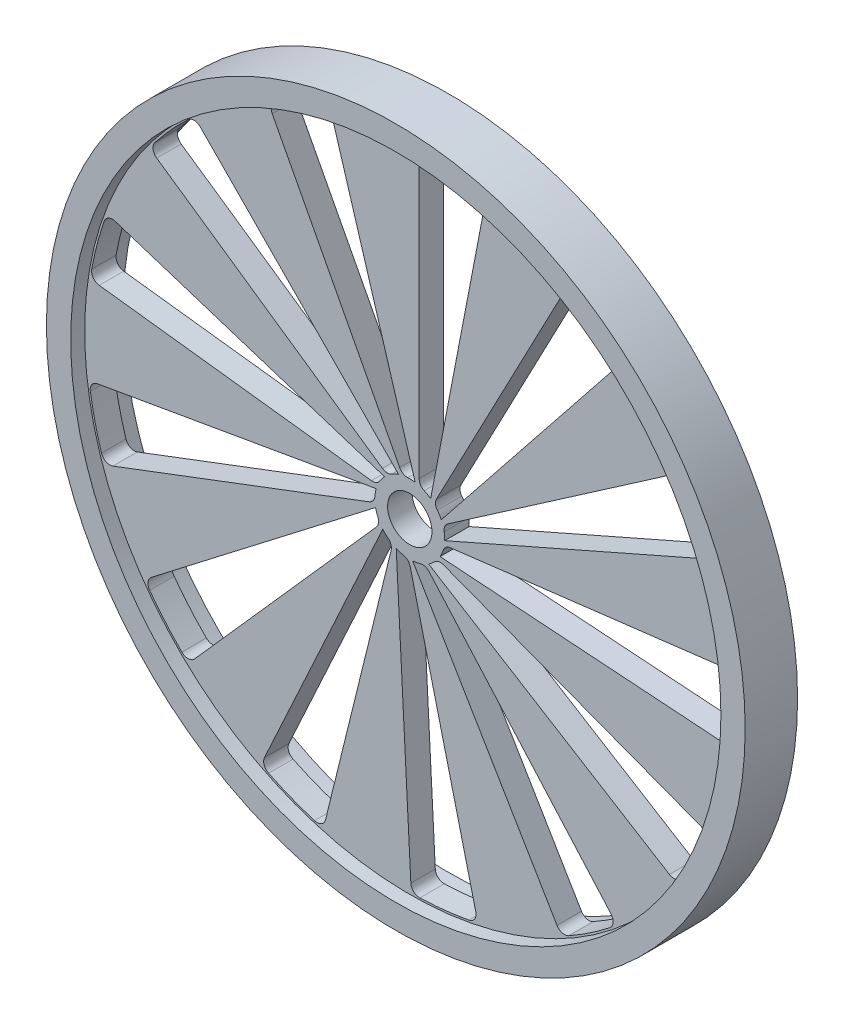
SolidWorks part; units mm, degrees
material "6061-T6 (SS)"
ref_plane "Front Plane" through (0, 0, 0) normal (0, 0, 1) x (1, 0, 0)
ref_plane "Top Plane" through (0, 0, 0) normal (0, 1, 0) x (1, 0, 0)
ref_plane "Right Plane" through (0, 0, 0) normal (1, 0, 0) x (0, 0, -1)
sketch "Sketch1" plane through (0, 0, 0) normal (0, 0, 1) x (1, 0, 0)
  line L0 (0, 319.656) -> (0, -338.2238) construction
  line L1 (-341.3059, 0) -> (522.3383, 0) construction
  line L2 (5.3734, 179.7008) -> (5.3734, 22.7463)
  line L3 (42.5198, 175.0831) -> (11.9457, 16.0406)
  line L4 (88.269, 156.6201) -> (15.3286, 17.6437)
  line L5 (119.0146, 135.2685) -> (18.0318, 8.6518)
  line L6 (150.9433, 97.6595) -> (21.7722, 8.4992)
  line L7 (168.2446, 64.4654) -> (19.9871, -0.7191)
  line L8 (179.0383, 16.3264) -> (23.2281, -2.5924)
  line L9 (178.9318, -21.1058) -> (17.3635, -9.9252)
  line L10 (166.1178, -68.747) -> (19.3627, -13.0901)
  line L11 (148.6278, -101.842) -> (10.7622, -16.8575)
  line L12 (115.1417, -138.0712) -> (11.0616, -20.589)
  line L13 (84.2751, -159.2474) -> (1.6954, -19.928)
  line L14 (37.788, -175.765) -> (0.2263, -23.3712)
  line L15 (0.6159, -180.1712) -> (-7.7598, -18.4333)
  line L16 (-48.2224, -173.1931) -> (-10.6608, -20.7994)
  line L17 (-83.1844, -159.8199) -> (-15.4374, -12.7157)
  line L18 (-123.1857, -130.9448) -> (-19.1056, -13.4626)
  line L19 (-147.9281, -102.8557) -> (-19.5784, -4.0851)
  line L20 (-169.9286, -58.6986) -> (-23.1736, -3.0418)
  line L21 (-178.7833, -22.3286) -> (-19.2342, 5.4814)
  line L22 (-177.7429, 26.9947) -> (-21.9328, 8.0759)
  line L23 (-168.6814, 63.3137) -> (-14.4837, 13.7921)
  line L24 (-144.8385, 106.5039) -> (-15.6674, 17.3435)
  line L25 (-119.9366, 134.4516) -> (-6.4152, 18.9432)
  line L26 (-78.7533, 161.6143) -> (-5.8129, 22.638)
  line L27 (-43.7158, 174.7883) -> (3.123, 19.7547)
  circle A0 centre (0, 0) radius 200
  circle A1 centre (0, 0) radius 12.7
  arc A3 (38.6544, 180.9167) -> (10.6615, 184.6925) centre (0, 0) ccw
  arc A4 (11.9457, 16.0406) -> (8.2987, 18.197) centre (0, 0) ccw
  arc A5 (42.5198, 175.0831) -> (38.6544, 180.9167) centre (37.6097, 176.027) ccw
  arc A6 (5.3734, 179.7008) -> (10.6615, 184.6925) centre (10.3734, 179.7008) cw
  arc A7 (5.3734, 22.7463) -> (8.2987, 18.197) centre (10.3734, 22.7463) ccw
  arc A8 (15.3286, 17.6437) -> (15.8047, 12.2561) centre (19.7559, 15.3201) ccw
  arc A9 (88.269, 156.6201) -> (95.2712, 158.5825) centre (92.6963, 154.2965) cw
  arc A10 (18.0318, 8.6518) -> (15.8047, 12.2561) centre (0, 0) ccw
  arc A11 (119.0146, 135.2685) -> (118.3029, 142.2301) centre (115.1056, 138.3861) ccw
  arc A12 (118.3029, 142.2301) -> (95.2712, 158.5825) centre (0, 0) ccw
  arc A13 (21.7722, 8.4992) -> (19.6901, 3.5074) centre (24.6126, 4.3843) ccw
  arc A14 (150.9433, 97.6595) -> (158.0554, 96.1431) centre (153.7836, 93.5446) cw
  arc A15 (19.9871, -0.7191) -> (19.6901, 3.5074) centre (0, 0) ccw
  arc A16 (168.2446, 64.4654) -> (170.8497, 70.9604) centre (166.2321, 69.0426) ccw
  arc A17 (170.8497, 70.9604) -> (158.0554, 96.1431) centre (0, 0) ccw
  arc A18 (23.2281, -2.5924) -> (19.0646, -6.0448) centre (23.8308, -7.556) ccw
  arc A19 (179.0383, 16.3264) -> (184.631, 11.6785) centre (179.641, 11.3628) cw
  arc A20 (17.3635, -9.9252) -> (19.0646, -6.0448) centre (0, 0) ccw
  arc A21 (178.9318, -21.1058) -> (184.2568, -16.5655) centre (179.2769, -16.1178) ccw
  arc A22 (184.2568, -16.5655) -> (184.631, 11.6785) centre (0, 0) ccw
  arc A23 (19.3627, -13.0901) -> (14.0718, -14.2122) centre (17.5897, -17.7652) ccw
  arc A24 (166.1178, -68.747) -> (168.9099, -75.4616) centre (164.3448, -73.4221) cw
  arc A25 (10.7622, -16.8575) -> (14.0718, -14.2122) centre (0, 0) ccw
  arc A26 (148.6278, -101.842) -> (155.453, -100.2964) centre (151.2515, -97.5857) ccw
  arc A27 (155.453, -100.2964) -> (168.9099, -75.4616) centre (0, 0) ccw
  arc A28 (11.0616, -20.589) -> (5.8552, -19.1237) centre (7.319, -23.9046) ccw
  arc A29 (115.1417, -138.0712) -> (114.4936, -145.3142) centre (111.3991, -141.3868) cw
  arc A30 (1.6954, -19.928) -> (5.8552, -19.1237) centre (0, 0) ccw
  arc A31 (84.2751, -159.2474) -> (91.0367, -161.0507) centre (88.5762, -156.698) ccw
  arc A32 (91.0367, -161.0507) -> (114.4936, -145.3142) centre (0, 0) ccw
  arc A33 (0.2263, -23.3712) -> (-3.7027, -19.6543) centre (-4.6284, -24.5678) ccw
  arc A34 (37.788, -175.765) -> (33.8481, -181.8772) centre (32.9333, -176.9616) cw
  arc A35 (-7.7598, -18.4333) -> (-3.7027, -19.6543) centre (0, 0) ccw
  arc A36 (0.6159, -180.1712) -> (5.765, -184.9102) centre (5.6092, -179.9126) ccw
  arc A37 (5.765, -184.9102) -> (33.8481, -181.8772) centre (0, 0) ccw
  arc A38 (-10.6608, -20.7994) -> (-12.4124, -15.6823) centre (-15.5155, -19.6028) ccw
  arc A39 (-48.2224, -173.1931) -> (-54.5515, -176.7742) centre (-53.0771, -171.9966) cw
  arc A40 (-15.4374, -12.7157) -> (-12.4124, -15.6823) centre (0, 0) ccw
  arc A41 (-83.1844, -159.8199) -> (-80.8274, -166.4089) centre (-78.6429, -161.9114) ccw
  arc A42 (-80.8274, -166.4089) -> (-54.5515, -176.7742) centre (0, 0) ccw
  arc A43 (-19.1056, -13.4626) -> (-18.2785, -8.1176) centre (-22.8481, -10.147) ccw
  arc A44 (-123.1857, -130.9448) -> (-130.4541, -131.1745) centre (-126.9283, -127.6292) cw
  arc A45 (-19.5784, -4.0851) -> (-18.2785, -8.1176) centre (0, 0) ccw
  arc A46 (-147.9281, -102.8557) -> (-148.9032, -109.7854) centre (-144.8788, -106.8183) ccw
  arc A47 (-148.9032, -109.7854) -> (-130.4541, -131.1745) centre (0, 0) ccw
  arc A48 (-23.1736, -3.0418) -> (-19.9573, 1.3066) centre (-24.9466, 1.6333) ccw
  arc A49 (-169.9286, -58.6986) -> (-176.4711, -55.5242) centre (-171.7017, -54.0235) cw
  arc A50 (-19.2342, 5.4814) -> (-19.9573, 1.3066) centre (0, 0) ccw
  arc A51 (-178.7833, -22.3286) -> (-182.8671, -28.0114) centre (-177.9247, -27.2544) ccw
  arc A52 (-182.8671, -28.0114) -> (-176.4711, -55.5242) centre (0, 0) ccw
  arc A53 (-21.9328, 8.0759) -> (-17.0641, 10.4316) centre (-21.3301, 13.0395) ccw
  arc A54 (-177.7429, 26.9947) -> (-182.0608, 32.846) centre (-177.1403, 31.9583) cw
  arc A55 (-14.4837, 13.7921) -> (-17.0641, 10.4316) centre (0, 0) ccw
  arc A56 (-168.6814, 63.3137) -> (-174.9383, 60.1797) centre (-170.2102, 58.5532) ccw
  arc A57 (-174.9383, 60.1797) -> (-182.0608, 32.846) centre (0, 0) ccw
  arc A58 (-15.6674, 17.3435) -> (-10.2617, 17.1668) centre (-12.8271, 21.4585) ccw
  arc A59 (-144.8385, 106.5039) -> (-145.9426, 113.6916) centre (-141.9982, 110.6188) cw
  arc A60 (-6.4152, 18.9432) -> (-10.2617, 17.1668) centre (0, 0) ccw
  arc A61 (-119.9366, 134.4516) -> (-126.9333, 134.5843) centre (-123.5027, 130.9469) ccw
  arc A62 (-126.9333, 134.5843) -> (-145.9426, 113.6916) centre (0, 0) ccw
  arc A63 (-5.8129, 22.638) -> (-1.1085, 19.9693) centre (-1.3856, 24.9616) ccw
  arc A64 (-78.7533, 161.6143) -> (-76.3906, 168.4918) centre (-74.326, 163.9379) cw
  arc A65 (3.123, 19.7547) -> (-1.1085, 19.9693) centre (0, 0) ccw
  arc A66 (-43.7158, 174.7883) -> (-49.8494, 178.1573) centre (-48.5021, 173.3423) ccw
  arc A67 (-49.8494, 178.1573) -> (-76.3906, 168.4918) centre (0, 0) ccw
  point P140 (0, 0)
  dimension "D1" = 400
  dimension "D2" = 25.4
  dimension "D3" = 5
  dimension "D4" = 370
  dimension "D5" = 5
  dimension "D6" = 13
extrude "Boss-Extrude1" add sketch "Sketch1" along normal blind 30
sketch "Sketch2" plane through (0, 0, 0) normal (0, 0, 1) x (1, 0, 0)
  circle A0 centre (0, 0) radius 186.1072
extrude "Cut-Extrude3" cut sketch "Sketch2" along normal blind 8
ref_plane "Plane2" through (0, 0, 15) normal (0, 0, 1) x (1, 0, 0)
mirror "Mirror1" about plane through (0, 0, 15) normal (0, 0, 1) of "Cut-Extrude3"
